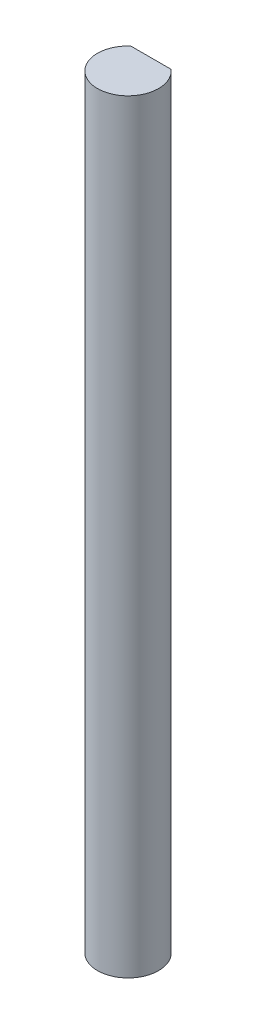
SolidWorks part; units mm, degrees
ref_plane "前视基准面" through (0, 0, 0) normal (0, 0, 1) x (1, 0, 0)
ref_plane "上视基准面" through (0, 0, 0) normal (0, 1, 0) x (1, 0, 0)
ref_plane "右视基准面" through (0, 0, 0) normal (1, 0, 0) x (0, 0, -1)
other "Configuration Table"
sketch "草图1" plane through (0, 0, 0) normal (0, 1, 0) x (1, 0, 0)
  line L0 (0, -4) -> (0, 4) construction
  line L1 (-2.6458, 3) -> (2.6458, 3)
  circle A0 centre (0, 0) radius 4
  dimension "D1" = 8
  dimension "D2" = 3
extrude "凸台-拉伸1" add sketch "草图1" along normal blind 100 contours A0 L0 L1 | L0 A0 L1
